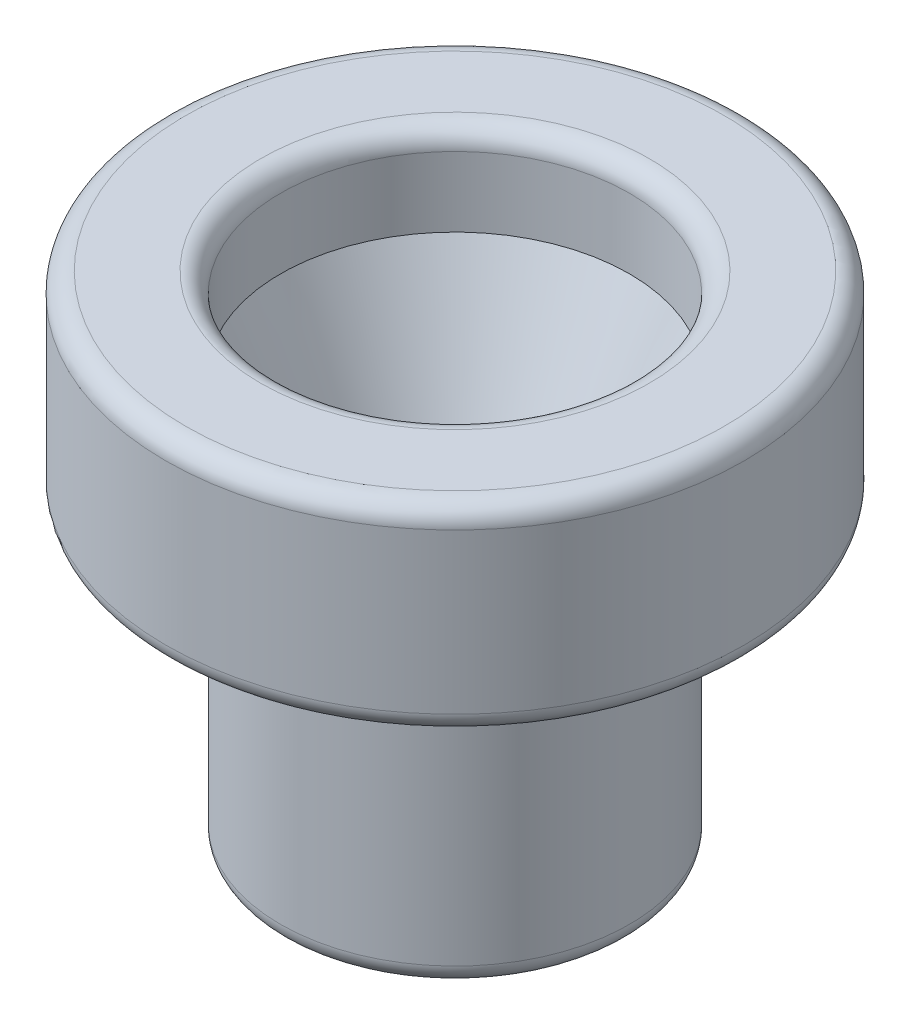
SolidWorks part; units mm, degrees
material "ABS"
ref_plane "Front Plane" through (0, 0, 0) normal (0, 0, 1) x (1, 0, 0)
ref_plane "Top Plane" through (0, 0, 0) normal (0, 1, 0) x (1, 0, 0)
ref_plane "Right Plane" through (0, 0, 0) normal (1, 0, 0) x (0, 0, -1)
sketch "Sketch1" plane through (0, 0, 0) normal (0, 0, 1) x (1, 0, 0)
  line L0 (13.335, 0) -> (13.335, 33.02)
  line L1 (13.335, 0) -> (22.225, 0)
  line L2 (0, 0) -> (0, 38.8139) construction
  line L3 (22.225, 0) -> (22.225, 38.1)
  line L4 (22.225, 38.1) -> (36.83, 38.1)
  line L5 (36.83, 38.1) -> (36.83, 63.5)
  line L6 (36.83, 63.5) -> (22.225, 63.5)
  line L7 (22.225, 63.5) -> (22.225, 52.07)
  line L9 (22.225, 52.07) -> (13.335, 33.02)
  dimension "D1" = 36.83
  dimension "D2" = 8.89
  dimension "D3" = 38.1
  dimension "D4" = 14.605
  dimension "D5" = 25.4
  dimension "D6" = 19.05
  dimension "D7" = 33.02
revolve "Revolve2" add sketch "Sketch1" angle 360 about L2
fillet "Fillet1" radius 2.54 5 edges at (0, 0, -22.225) (0, 38.1, -36.83) (0, 33.02, -13.335) (0, 63.5, -22.225) (0, 63.5, -36.83)
